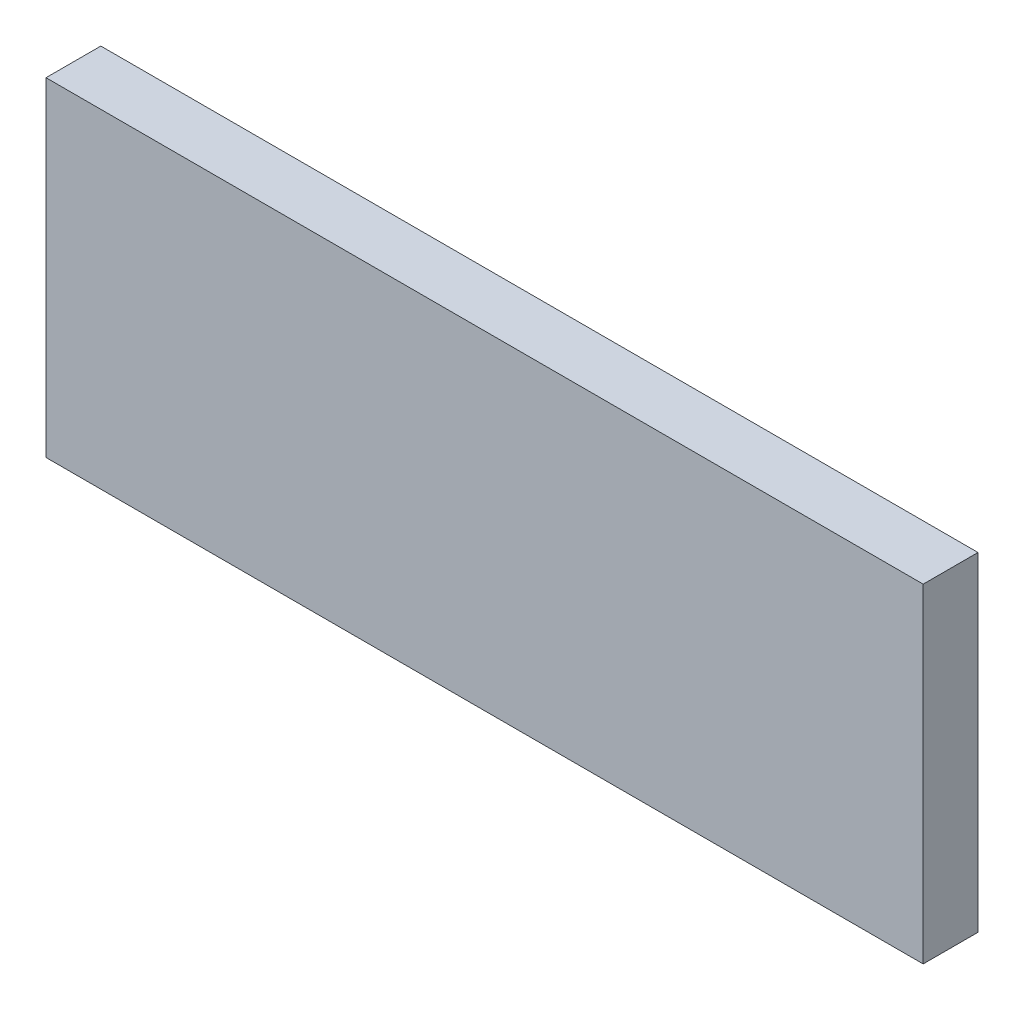
SolidWorks part; units mm, degrees
ref_plane "Plan de face" through (0, 0, 0) normal (0, 0, 1) x (1, 0, 0)
ref_plane "Plan de dessus" through (0, 0, 0) normal (0, 1, 0) x (1, 0, 0)
ref_plane "Plan de droite" through (0, 0, 0) normal (1, 0, 0) x (0, 0, -1)
sketch "Esquisse1" plane through (0, 0, 0) normal (0, 0, 1) x (1, 0, 0)
  line L1 (-101.6, -38.1) -> (101.6, -38.1)
  line L2 (-101.6, -38.1) -> (-101.6, 38.1)
  line L3 (-101.6, 38.1) -> (101.6, 38.1)
  line L4 (101.6, -38.1) -> (101.6, 38.1)
  line L5 (-101.6, -38.1) -> (101.6, 38.1) construction
  line L6 (-101.6, 38.1) -> (101.6, -38.1) construction
  point P0 (0, 0)
  dimension "D1" = 203.2
  dimension "D2" = 76.2
extrude "Boss.-Extru.1" add sketch "Esquisse1" along normal blind 12.7
